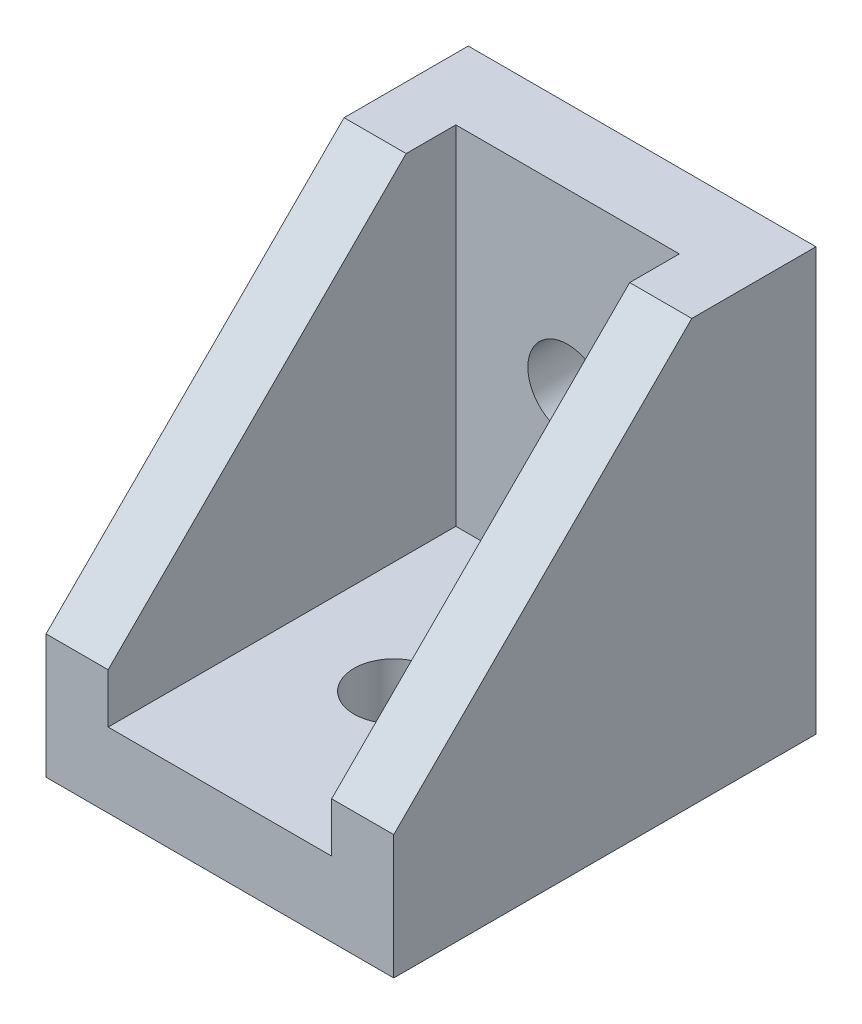
SolidWorks part; units mm, degrees
ref_plane "Front Plane" through (0, 0, 0) normal (0, 0, 1) x (1, 0, 0)
ref_plane "Top Plane" through (0, 0, 0) normal (0, 1, 0) x (1, 0, 0)
ref_plane "Right Plane" through (0, 0, 0) normal (1, 0, 0) x (0, 0, -1)
sketch "Sketch1" plane through (0, 0, 0) normal (0, 1, 0) x (1, 0, 0)
  line L1 (-7, -7) -> (7, -7)
  line L2 (-7, -7) -> (-7, 7)
  line L3 (-7, 7) -> (7, 7)
  line L4 (7, -7) -> (7, 7)
  line L5 (-7, -7) -> (7, 7) construction
  line L6 (-7, 7) -> (7, -7) construction
  circle A0 centre (0, 0) radius 1.6
  point P0 (0, 0)
  dimension "D1" = 3.2
  dimension "D2" = 14
extrude "Boss-Extrude1" add sketch "Sketch1" along normal blind 3
sketch "Sketch2" plane through (0, 0, -7) normal (0, 0, -1) x (-1, 0, 0)
  line L0 (-7, 3) -> (-7, 0)
  line L2 (-7, 3) -> (-7, 17)
  line L3 (-7, 17) -> (7, 17)
  line L4 (7, 3) -> (7, 17)
  line L5 (-7, 3) -> (7, 17) construction
  line L6 (-7, 17) -> (7, 3) construction
  line L7 (7.7, 0) -> (-7.7, 0) construction
  line L8 (-7, 0) -> (7, 0)
  line L9 (7, 3) -> (7, 0) construction
  line L10 (7, 0) -> (7, 3)
  circle A0 centre (0, 10) radius 1.6
  point P0 (0, 10)
  dimension "D1" = 3.2
extrude "Boss-Extrude2" add sketch "Sketch2" along normal blind 3
sketch "Sketch5" plane through (0, 0, 0) normal (1, 0, 0) x (0, 0, -1)
  line L0 (7, 17) -> (5, 17)
  line L1 (5, 17) -> (-7, 5)
  line L2 (-7, 5) -> (-7, 3)
  line L3 (-7, 3) -> (7, 3)
  line L4 (7, 3) -> (7, 17)
  dimension "D1" = 2
extrude "Boss-Extrude3" add sketch "Sketch5" against normal blind 2.5 from offset 4.5 offset against normal yes
mirror "Mirror2" about plane through (0, 0, 0) normal (1, 0, 0) of "Boss-Extrude3"
